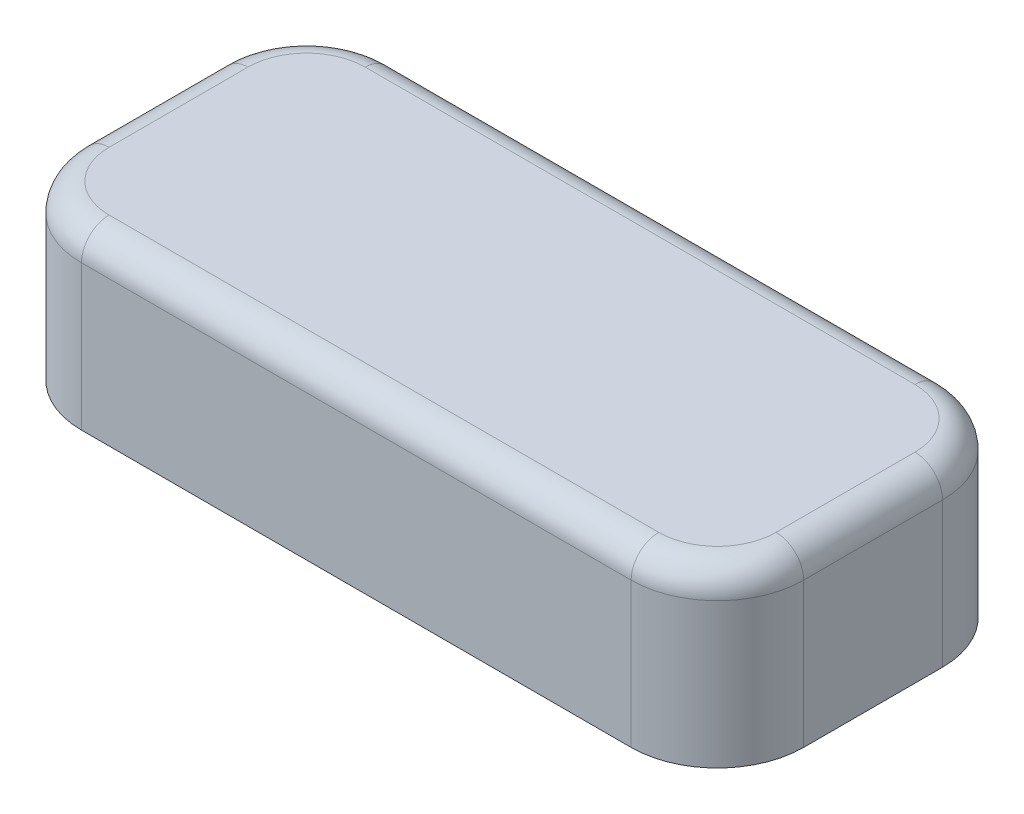
SolidWorks part; units mm, degrees
ref_plane "前视基准面" through (0, 0, 0) normal (0, 0, 1) x (1, 0, 0)
ref_plane "上视基准面" through (0, 0, 0) normal (0, 1, 0) x (1, 0, 0)
ref_plane "右视基准面" through (0, 0, 0) normal (1, 0, 0) x (0, 0, -1)
other "Configuration Table"
sketch "草图1" plane through (0, 0, 0) normal (0, 1, 0) x (1, 0, 0)
  line L0 (-2.2, 0) -> (2.2, 0) construction
  line L1 (0, 2.2) -> (0, -2.2) construction
  line L2 (2.2, 0.6) -> (2.2, -0.6)
  line L3 (-0.6, 2.2) -> (0.6, 2.2)
  line L4 (-2.2, -0.6) -> (-2.2, 0.6)
  line L5 (-0.6, -2.2) -> (0.6, -2.2)
  line L6 (-0.6, 2.2) -> (-0.6, 0.6)
  line L7 (-0.6, 0.6) -> (-2.2, 0.6)
  line L8 (-2.2, -0.6) -> (-0.6, -0.6)
  line L9 (-0.6, -0.6) -> (-0.6, -2.2)
  line L10 (0.6, -2.2) -> (0.6, -0.6)
  line L11 (0.6, -0.6) -> (2.2, -0.6)
  line L12 (2.2, 0.6) -> (0.6, 0.6)
  line L13 (0.6, 0.6) -> (0.6, 2.2)
  line L14 (-11.9062, 0) -> (11.9062, 0) construction
  line L15 (-14.1063, 0) -> (-9.7062, 0) construction
  line L16 (-11.9062, 2.2) -> (-11.9062, -2.2) construction
  line L17 (-14.1063, -0.6) -> (-14.1063, 0.6)
  line L18 (-12.5062, -2.2) -> (-11.3063, -2.2)
  line L19 (-11.3063, 2.2) -> (-12.5062, 2.2)
  line L20 (-9.7062, -0.6) -> (-9.7062, 0.6)
  line L21 (-14.1063, -0.6) -> (-12.5062, -0.6)
  line L22 (-12.5062, -0.6) -> (-12.5062, -2.2)
  line L23 (-11.3063, -2.2) -> (-11.3063, -0.6)
  line L24 (-11.3063, -0.6) -> (-9.7062, -0.6)
  line L25 (-9.7062, 0.6) -> (-11.3063, 0.6)
  line L26 (-11.3063, 0.6) -> (-11.3063, 2.2)
  line L27 (-12.5062, 2.2) -> (-12.5062, 0.6)
  line L28 (-12.5062, 0.6) -> (-14.1063, 0.6)
  line L29 (9.7062, 0) -> (14.1063, 0) construction
  line L30 (11.9062, -2.2) -> (11.9062, 2.2) construction
  line L31 (9.7062, 0.6) -> (9.7062, -0.6)
  line L32 (11.3063, 2.2) -> (12.5062, 2.2)
  line L33 (14.1063, -0.6) -> (14.1063, 0.6)
  line L34 (11.3063, -2.2) -> (12.5062, -2.2)
  line L35 (9.7062, 0.6) -> (11.3063, 0.6)
  line L36 (11.3063, 0.6) -> (11.3063, 2.2)
  line L37 (12.5062, 2.2) -> (12.5062, 0.6)
  line L38 (12.5062, 0.6) -> (14.1063, 0.6)
  line L39 (14.1063, -0.6) -> (12.5062, -0.6)
  line L40 (12.5062, -0.6) -> (12.5062, -2.2)
  line L41 (11.3063, -2.2) -> (11.3063, -0.6)
  line L42 (11.3063, -0.6) -> (9.7062, -0.6)
  circle A0 centre (0, 0) radius 2.8
  circle A1 centre (-11.9062, 0) radius 2.8
  circle A2 centre (11.9062, 0) radius 2.8
  point P4 (0, 0)
  point P7 (0, 0)
  point P10 (2.2, 0)
  point P13 (0, 2.2)
  point P16 (-2.2, 0)
  point P19 (0, -2.2)
  point P28 (0, 0)
  point P31 (-11.9062, 0)
  point P34 (-11.9062, 0)
  point P37 (-14.1063, 0)
  point P40 (-11.9062, -2.2)
  point P43 (-11.9062, 2.2)
  point P46 (-9.7062, 0)
  point P54 (11.9062, 0)
  point P57 (11.9062, 0)
  point P60 (9.7062, 0)
  point P63 (11.9062, 2.2)
  point P66 (14.1063, 0)
  point P69 (11.9062, -2.2)
  dimension "D7" = 5.6
  dimension "D15" = 5.6
  dimension "D22" = 5.6
  dimension "D1" = 4.4
  dimension "D2" = 4.4
  dimension "D3" = 1.2
  dimension "D4" = 1.2
  dimension "D5" = 1.2
  dimension "D6" = 1.2
  dimension "D8" = 23.8125
  dimension "D9" = 4.4
  dimension "D10" = 4.4
  dimension "D11" = 1.2
  dimension "D12" = 1.2
  dimension "D13" = 1.2
  dimension "D14" = 1.2
  dimension "D16" = 4.4
  dimension "D17" = 4.4
  dimension "D18" = 1.2
  dimension "D19" = 1.2
  dimension "D20" = 1.2
  dimension "D21" = 1.2
extrude "凸台-拉伸1" add sketch "草图1" against normal blind 8
sketch "草图2" plane through (0, 0, 0) normal (0, 1, 0) x (1, 0, 0)
  line L0 (0, -9.025) -> (0, 9.025) construction
  line L1 (-20.9312, 9.025) -> (20.9312, 9.025)
  line L2 (-20.9312, -9.025) -> (20.9312, -9.025)
  line L3 (-20.9312, 9.025) -> (-20.9312, -9.025)
  line L4 (20.9312, 9.025) -> (20.9312, -9.025)
  point P4 (0, 0)
  point P8 (0, 9.025)
  point P11 (0, -9.025)
  dimension "D1" = 18.05
  dimension "D2" = 41.8625
extrude "凸台-拉伸2" add sketch "草图2" along normal blind 1
sketch "草图3" plane through (0, 0, 0) normal (0, 1, 0) x (1, 0, 0)
  line L4 (20.9312, -9.025) -> (20.9312, 9.025)
  line L5 (-20.9312, -9.025) -> (20.9312, -9.025)
  line L6 (-20.9312, 9.025) -> (-20.9312, -9.025)
  line L7 (20.9312, 9.025) -> (-20.9312, 9.025)
  line L8 (20.9312, -9.025) -> (20.9312, 9.025)
  line L9 (-20.9312, -9.025) -> (20.9312, -9.025)
  line L10 (-20.9312, 9.025) -> (-20.9312, -9.025)
  line L11 (20.9312, 9.025) -> (-20.9312, 9.025)
  line L20 (19.9312, -8.025) -> (19.9312, 8.025)
  line L21 (19.9312, 8.025) -> (-19.9312, 8.025)
  line L22 (-19.9312, 8.025) -> (-19.9312, -8.025)
  line L23 (-19.9312, -8.025) -> (19.9312, -8.025)
  line L24 (19.9312, -8.025) -> (19.9312, 8.025)
  line L25 (19.9312, 8.025) -> (-19.9312, 8.025)
  line L26 (-19.9312, 8.025) -> (-19.9312, -8.025)
  line L27 (-19.9312, -8.025) -> (19.9312, -8.025)
  dimension "D1" = 0
  dimension "D2" = 1
extrude "凸台-拉伸3" add sketch "草图3" against normal blind 9
sketch "草图4" plane through (0, 0, 0) normal (0, 1, 0) x (1, 0, 0)
  line L0 (9.7062, 0.6) -> (9.7062, -0.6) construction
  line L1 (12.5062, 2.2) -> (11.3063, 2.2) construction
  line L2 (11.3063, -2.2) -> (12.5062, -2.2) construction
  line L3 (14.1063, -0.6) -> (14.1063, 0.6) construction
  line L4 (2.2, -0.6) -> (2.2, 0.6) construction
  line L5 (0.6, 2.2) -> (-0.6, 2.2) construction
  line L6 (-2.2, 0.6) -> (-2.2, -0.6) construction
  line L7 (-0.6, -2.2) -> (0.6, -2.2) construction
  line L8 (-11.3063, 2.2) -> (-12.5062, 2.2) construction
  line L9 (-9.7062, -0.6) -> (-9.7062, 0.6) construction
  line L10 (-12.5062, -2.2) -> (-11.3063, -2.2) construction
  line L11 (-14.1063, 0.6) -> (-14.1063, -0.6) construction
  line L12 (9.7062, 0.6) -> (9.7062, -0.6)
  line L13 (12.5062, 2.2) -> (11.3063, 2.2)
  line L14 (11.3063, -2.2) -> (12.5062, -2.2)
  line L15 (14.1063, -0.6) -> (14.1063, 0.6)
  line L16 (2.2, -0.6) -> (2.2, 0.6)
  line L17 (0.6, 2.2) -> (-0.6, 2.2)
  line L18 (-2.2, 0.6) -> (-2.2, -0.6)
  line L19 (-0.6, -2.2) -> (0.6, -2.2)
  line L20 (-11.3063, 2.2) -> (-12.5062, 2.2)
  line L21 (-9.7062, -0.6) -> (-9.7062, 0.6)
  line L22 (-12.5062, -2.2) -> (-11.3063, -2.2)
  line L23 (-14.1063, 0.6) -> (-14.1063, -0.6)
  line L24 (-14.1063, -0.6) -> (-19.9312, -0.6)
  line L25 (-19.9312, 8.025) -> (-19.9312, -8.025) construction
  line L26 (-19.9312, -0.6) -> (-19.9312, 0.6)
  line L27 (-19.9312, 8.025) -> (-19.9312, -8.025) construction
  line L28 (-19.9312, 0.6) -> (-14.1063, 0.6)
  line L29 (-12.5062, -2.2) -> (-12.5062, -8.025)
  line L30 (-19.9312, -8.025) -> (19.9312, -8.025) construction
  line L31 (-12.5062, -8.025) -> (-11.3063, -8.025)
  line L32 (-19.9312, -8.025) -> (19.9312, -8.025) construction
  line L33 (-11.3063, -8.025) -> (-11.3063, -2.2)
  line L34 (-12.5062, 2.2) -> (-12.5062, 8.025)
  line L35 (19.9312, 8.025) -> (-19.9312, 8.025) construction
  line L36 (-12.5062, 8.025) -> (-11.3063, 8.025)
  line L37 (19.9312, 8.025) -> (-19.9312, 8.025) construction
  line L38 (-11.3063, 8.025) -> (-11.3063, 2.2)
  line L39 (-9.7062, -0.6) -> (-2.2, -0.6)
  line L40 (-2.2, 0.6) -> (-9.7062, 0.6)
  line L41 (-0.6, -2.2) -> (-0.6, -8.025)
  line L42 (-0.6, -8.025) -> (0.6, -8.025)
  line L43 (0.6, -8.025) -> (0.6, -2.2)
  line L44 (2.2, -0.6) -> (9.7062, -0.6)
  line L45 (9.7062, 0.6) -> (2.2, 0.6)
  line L46 (0.6, 2.2) -> (0.6, 8.025)
  line L47 (0.6, 8.025) -> (-0.6, 8.025)
  line L48 (-0.6, 8.025) -> (-0.6, 2.2)
  line L49 (11.3063, -2.2) -> (11.3063, -8.025)
  line L50 (11.3063, -8.025) -> (12.5062, -8.025)
  line L51 (12.5062, -8.025) -> (12.5062, -2.2)
  line L52 (14.1063, -0.6) -> (19.9312, -0.6)
  line L53 (19.9312, -8.025) -> (19.9312, 8.025) construction
  line L54 (19.9312, -0.6) -> (19.9312, 0.6)
  line L55 (19.9312, 0.6) -> (14.1063, 0.6)
  line L56 (12.5062, 2.2) -> (12.5062, 8.025)
  line L57 (12.5062, 8.025) -> (11.3062, 8.025)
  line L58 (11.3062, 8.025) -> (11.3063, 2.2)
extrude "凸台-拉伸4" add sketch "草图4" against normal blind 2.5
fillet "圆角1" radius 5 8 edges at (20.9312, -4, -9.025) (20.9312, -4, 9.025) (-20.9312, -4, -9.025) (-20.9312, -4, 9.025) (19.9312, -4.5, -8.025) (19.9312, -4.5, 8.025) (-19.9312, -4.5, -8.025) (-19.9312, -4.5, 8.025)
fillet "圆角2" radius 1.6 24 edges at (-13.7187, 0, 8.025) (-19.9312, 0, 1.8125) (-19.9312, 0, -1.8125) (-13.7187, 0, -8.025) (13.7187, 0, -8.025) (19.9312, 0, -1.8125) (19.9312, 0, 1.8125) (13.7187, 0, 8.025) (19.4668, 1, -7.5605) (20.9312, 1, 0) (19.4668, 1, 7.5605) (0, 1, 9.025) (-19.4668, 1, 7.5605) (-20.9312, 1, 0) (-19.4668, 1, -7.5605) (-18.4668, 0, 6.5605) (-18.4668, 0, -6.5605) (18.4668, 0, -6.5605) (18.4668, 0, 6.5605) (5.9531, 0, 8.025) (-5.9531, 0, 8.025) (-5.9531, 0, -8.025) (5.9531, 0, -8.025) (0, 1, -9.025)
